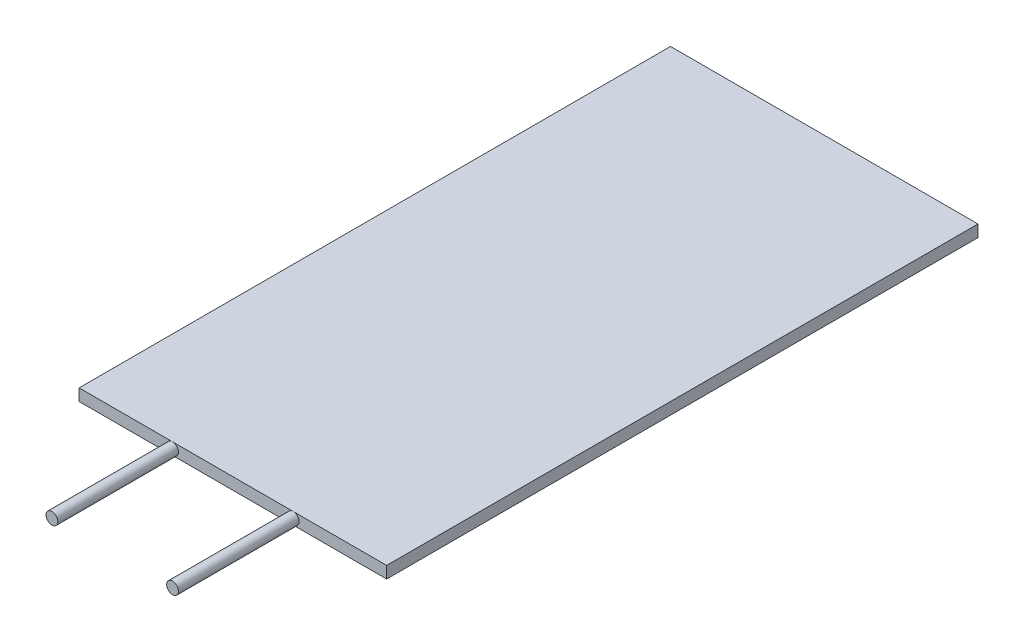
SolidWorks part; units mm, degrees
ref_plane "PLN_FRONT" through (0, 0, 0) normal (0, 0, 1) x (1, 0, 0)
ref_plane "PLN_TOP" through (0, 0, 0) normal (0, 1, 0) x (1, 0, 0)
ref_plane "PLN_RIGHT" through (0, 0, 0) normal (1, 0, 0) x (0, 0, -1)
sketch "Sketch1" plane through (0, 0, 0) normal (0, 1, 0) x (1, 0, 0)
  line L1 (-6.5, -12.5) -> (6.5, -12.5)
  line L2 (-6.5, -12.5) -> (-6.5, 12.5)
  line L3 (-6.5, 12.5) -> (6.5, 12.5)
  line L4 (6.5, -12.5) -> (6.5, 12.5)
  line L5 (-6.5, -12.5) -> (6.5, 12.5) construction
  line L6 (-6.5, 12.5) -> (6.5, -12.5) construction
  point P0 (0, 0)
  dimension "D1" = 25
  dimension "D2" = 13
extrude "Boss-Extrude1" add sketch "Sketch1" along normal blind 0.5
sketch "Sketch2" plane through (0, 0, 12.5) normal (0, 0, 1) x (1, 0, 0)
  line L0 (-2.55, 0.25) -> (2.55, 0.25) construction
  line L1 (6.5, 0.5) -> (6.5, 0) construction
  line L2 (-6.5, 0) -> (6.5, 0) construction
  circle A0 centre (-2.55, 0.25) radius 0.25
  circle A1 centre (2.55, 0.25) radius 0.25
  point P4 (0, 0.25)
  point P9 (6.5, 0.25)
  dimension "D1" = 5.1
extrude "Boss-Extrude2" add sketch "Sketch2" along normal blind 5.1
